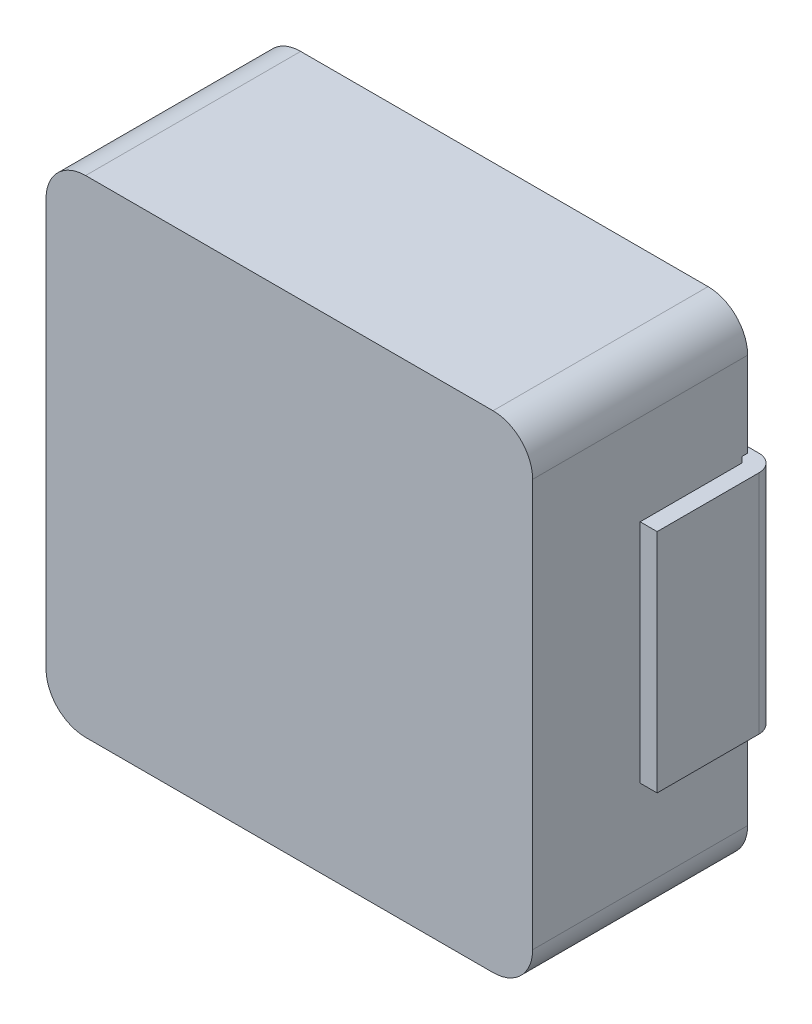
SolidWorks part; units mm, degrees
ref_plane "Front Plane" through (0, 0, 0) normal (0, 0, 1) x (1, 0, 0)
ref_plane "Top Plane" through (0, 0, 0) normal (0, 1, 0) x (1, 0, 0)
ref_plane "Right Plane" through (0, 0, 0) normal (1, 0, 0) x (0, 0, -1)
sketch "Sketch1" plane through (0, 0, 0) normal (0, 0, 1) x (1, 0, 0)
  line L1 (-2.15, 2.15) -> (2.15, 2.15)
  line L2 (-2.15, 2.15) -> (-2.15, -2.15)
  line L3 (-2.15, -2.15) -> (2.15, -2.15)
  line L4 (2.15, 2.15) -> (2.15, -2.15)
  line L5 (-2.15, 2.15) -> (2.15, -2.15) construction
  line L6 (-2.15, -2.15) -> (2.15, 2.15) construction
  point P0 (0, 0)
  dimension "D1" = 4.3
  dimension "D2" = 4.3
extrude "Boss-Extrude1" add sketch "Sketch1" along normal blind 1.9
fillet "Fillet1" radius 0.35 4 edges at (2.15, 2.15, 0.95) (-2.15, 2.15, 0.95) (2.15, -2.15, 0.95) (-2.15, -2.15, 0.95)
sketch "Sketch2" plane through (0, 0, 0) normal (0, 0, -1) x (-1, 0, 0)
  line L0 (2.15, 1.8) -> (2.15, -1.8) construction
  line L1 (2.15, -1.05) -> (1.25, -1.05)
  line L2 (2.15, -1.05) -> (2.15, 1.05)
  line L3 (2.15, 1.05) -> (1.25, 1.05)
  line L4 (1.25, -1.05) -> (1.25, 1.05)
  line L5 (2.15, -1.05) -> (1.25, 1.05) construction
  line L6 (2.15, 1.05) -> (1.25, -1.05) construction
  line L7 (-2.15, -1.8) -> (-2.15, 1.8) construction
  line L8 (-2.15, -1.05) -> (-1.25, -1.05)
  line L9 (-2.15, -1.05) -> (-2.15, 1.05)
  line L10 (-2.15, 1.05) -> (-1.25, 1.05)
  line L11 (-1.25, -1.05) -> (-1.25, 1.05)
  line L12 (-2.15, -1.05) -> (-1.25, 1.05) construction
  line L13 (-2.15, 1.05) -> (-1.25, -1.05) construction
  point P4 (1.7, 0)
  point P11 (-1.7, 0)
  point P14 (1.25, 0)
  point P16 (-1.25, 0)
  point P17 (1.2476, 0.8335)
  dimension "D1" = 0.9
  dimension "D2" = 2.1
extrude "Cut-Extrude1" cut sketch "Sketch2" against normal blind 0.05
sketch "Sketch3" plane through (0, 0, 0.05) normal (0, 0, -1) x (-1, 0, 0)
  line L0 (2.15, -1.05) -> (2.15, 1.05) construction
  line L1 (1.3, -1) -> (2.3, -1)
  line L2 (1.3, -1) -> (1.3, 1)
  line L3 (1.3, 1) -> (2.3, 1)
  line L4 (2.3, -1) -> (2.3, 1)
  line L5 (1.3, -1) -> (2.3, 1) construction
  line L6 (1.3, 1) -> (2.3, -1) construction
  line L7 (-1.3, -1) -> (-2.3, -1)
  line L8 (-1.3, -1) -> (-1.3, 1)
  line L9 (-1.3, 1) -> (-2.3, 1)
  line L10 (-2.3, -1) -> (-2.3, 1)
  line L11 (-1.3, -1) -> (-2.3, 1) construction
  line L12 (-1.3, 1) -> (-2.3, -1) construction
  line L13 (-2.15, 1.05) -> (-2.15, -1.05) construction
  point P4 (1.8, 0)
  point P9 (-1.8, 0)
  point P10 (0, 0)
  dimension "D1" = 1
  dimension "D2" = 2
  dimension "D3" = 0.15
  dimension "D4" = 0.15
extrude "Boss-Extrude2" add sketch "Sketch3" along normal blind 0.15
sketch "Sketch4" plane through (0, 0, 0.05) normal (0, 0, 1) x (1, 0, 0)
  line L1 (-2.3, -1) -> (-2.15, -1)
  line L2 (-2.3, -1) -> (-2.3, 1)
  line L3 (-2.3, 1) -> (-2.15, 1)
  line L4 (-2.15, -1) -> (-2.15, 1)
  line L5 (-2.3, -1) -> (-2.15, 1) construction
  line L6 (-2.3, 1) -> (-2.15, -1) construction
  line L7 (2.3, -1) -> (2.15, -1)
  line L8 (2.3, -1) -> (2.3, 1)
  line L9 (2.3, 1) -> (2.15, 1)
  line L10 (2.15, -1) -> (2.15, 1)
  line L11 (2.3, -1) -> (2.15, 1) construction
  line L12 (2.3, 1) -> (2.15, -1) construction
  point P4 (-2.225, 0)
  point P11 (2.225, 0)
extrude "Boss-Extrude3" add sketch "Sketch4" along normal blind 0.9
fillet "Fillet2" radius 0.15 2 edges at (2.3, 0, -0.1) (-2.3, 0, -0.1)
equation "\"D4@Sketch3\"=\"D3@Sketch3\""
